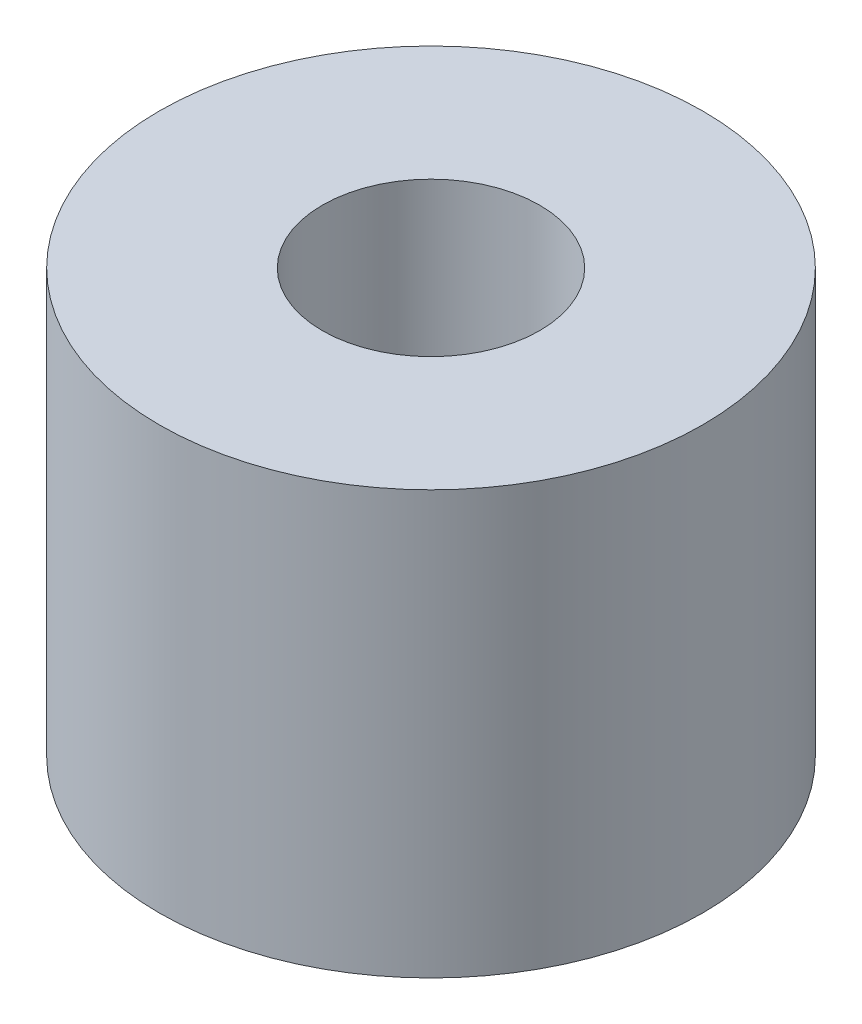
SolidWorks part; units mm, degrees
ref_plane "Alzado" through (0, 0, 0) normal (0, 0, 1) x (1, 0, 0)
ref_plane "Planta" through (0, 0, 0) normal (0, 1, 0) x (1, 0, 0)
ref_plane "Vista lateral" through (0, 0, 0) normal (1, 0, 0) x (0, 0, -1)
sketch "Croquis1" plane through (0, 0, 0) normal (0, 1, 0) x (1, 0, 0)
  circle A0 centre (0, 0) radius 4.5
  circle A1 centre (0, 0) radius 1.8
  dimension "D1" = 9
  dimension "D2" = 3.6
extrude "Saliente-Extruir1" add sketch "Croquis1" along normal blind 7
